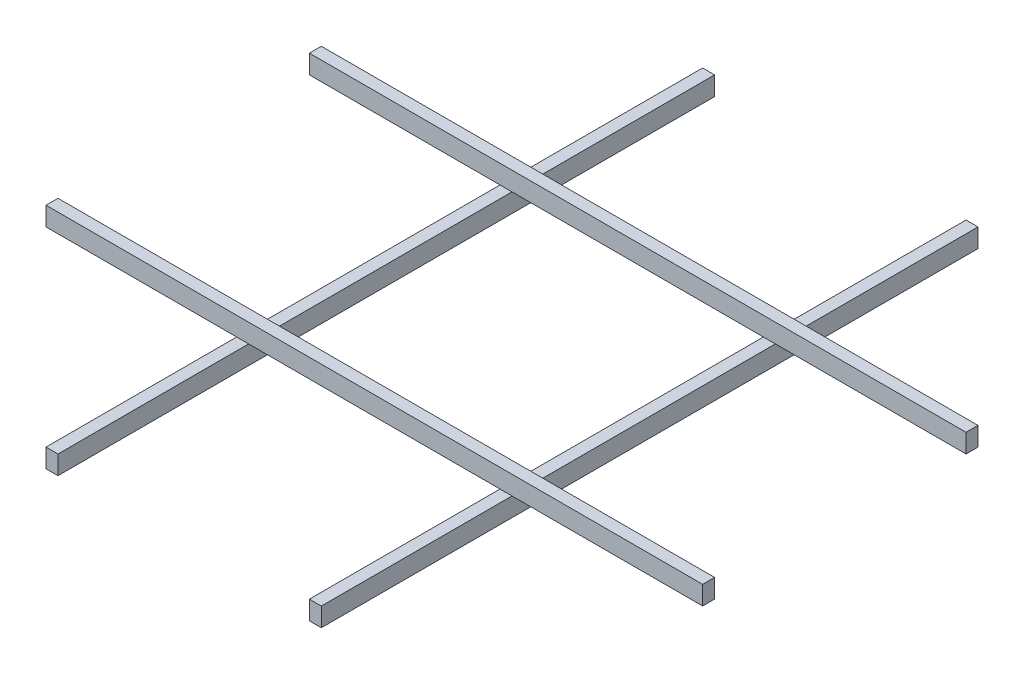
SolidWorks part; units mm, degrees
material "Doug Fir"
ref_plane "Front Plane" through (0, 0, 0) normal (0, 0, 1) x (1, 0, 0)
ref_plane "Top Plane" through (0, 0, 0) normal (0, 1, 0) x (1, 0, 0)
ref_plane "Right Plane" through (0, 0, 0) normal (1, 0, 0) x (0, 0, -1)
sketch "Lower Level" plane through (0, 0, 0) normal (0, 1, 0) x (1, 0, 0)
  line L0 (1155.7, 0) -> (1155.7, 4876.8)
  line L1 (3111.5, 0) -> (3111.5, 4876.8)
  line L2 (1155.7, 2438.4) -> (3111.5, 2438.4) construction
  point P7 (2133.6, 2438.4)
  dimension "D1" = 4876.8
  dimension "D2" = 977.9
ref_plane "Plane2" through (0, 139.7, 0) normal (0, 1, 0) x (1, 0, 0)
sketch "Sketch12" plane through (0, 139.7, 0) normal (0, 1, 0) x (1, 0, 0)
  line L0 (-304.8, 3416.3) -> (4572, 3416.3)
  line L1 (4572, 1460.5) -> (-304.8, 1460.5)
  line L2 (2133.6, 3416.3) -> (2133.6, 1460.5) construction
  point P0 (2133.6, 2438.4)
  point P6 (2133.6, 1460.5)
  point P7 (2133.6, 3416.3)
  point P10 (2133.6, 2438.4)
  dimension "D1" = 4876.8
  dimension "D2" = 977.9
other "Profiles 4X6(1)"
ref_plane "Plane1" through (1155.7, 0, 0) normal (0, 0, -1) x (-1, 0, 0)
sketch "Sketch1" plane through (1155.7, 0, 0) normal (0, 0, -1) x (-1, 0, 0)
  line L1 (-44.45, 69.85) -> (44.45, 69.85)
  line L2 (-44.45, 69.85) -> (-44.45, -69.85)
  line L3 (-44.45, -69.85) -> (44.45, -69.85)
  line L4 (44.45, 69.85) -> (44.45, -69.85)
  line L5 (-44.45, 69.85) -> (44.45, -69.85) construction
  line L6 (-44.45, -69.85) -> (44.45, 69.85) construction
  point P0 (0, 0)
  point P6 (0, 69.85)
  point P7 (0, -69.85)
  point P8 (44.45, 0)
  point P9 (-44.45, 0)
  point P10 (0, 0)
  dimension "D1" = 88.9
  dimension "D2" = 139.7
sketch3d "3DSketch2"
  line L0 (2133.6, 139.7, -2438.4) -> (2133.6, 0, -2438.4)
  line L1 (1155.7, 0, -2438.4) -> (3111.5, 0, -2438.4) construction
equation "\"Width\" = 38.5"
equation "\"Length\"=192"
equation "\"D1@Lower Level\"=\"Length\""
equation "\"D2@Lower Level\"=\"Width\""
equation "\"D1@Sketch12\"=\"Length\""
equation "\"D2@Sketch12\"=\"Width\""
